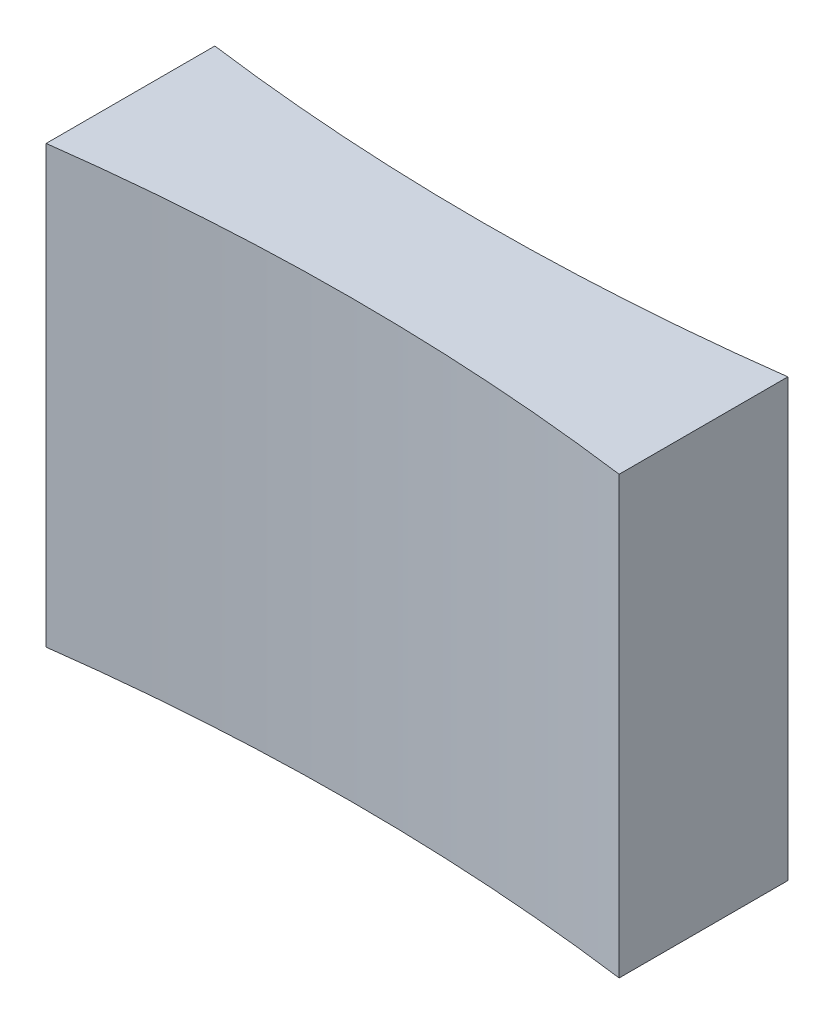
SolidWorks part; units mm, degrees
ref_plane "Front Plane" through (0, 0, 0) normal (0, 0, 1) x (1, 0, 0)
ref_plane "Top Plane" through (0, 0, 0) normal (0, 1, 0) x (1, 0, 0)
ref_plane "Right Plane" through (0, 0, 0) normal (1, 0, 0) x (0, 0, -1)
sketch "Sketch2" plane through (0, 0, 0) normal (0, 1, 0) x (1, 0, 0)
  line L0 (13.1344, -3.8671) -> (13.1344, 3.8671)
  line L1 (-13.1344, 3.8671) -> (-13.1344, -3.8671)
  line L2 (-13.1344, -3.8671) -> (-13.1344, 3.8671)
  line L3 (13.1344, 3.8671) -> (13.1344, -3.8671)
  arc A0 (13.1344, -3.8671) -> (-13.1344, -3.8671) centre (0, -102.9074) ccw
  arc A1 (-13.1344, 3.8671) -> (13.1344, 3.8671) centre (0, 102.9074) ccw
  arc A2 (-13.1344, -3.8671) -> (-29.3195, -7.399) centre (0, -102.9074) ccw
  arc A3 (-29.3195, 7.399) -> (-13.1344, 3.8671) centre (0, 102.9074) ccw
  arc A4 (-29.3195, 7.399) -> (-31.2047, 7.8764) centre (-35.047, -11.2583) ccw
  arc A5 (-31.2047, -7.8764) -> (-31.2047, 7.8764) centre (-41.547, 0) ccw
  arc A6 (-31.2047, -7.8764) -> (-29.3195, -7.399) centre (-35.047, 11.2583) ccw
  arc A7 (13.1344, 3.8671) -> (29.3195, 7.399) centre (0, 102.9074) ccw
  arc A8 (29.3195, -7.399) -> (13.1344, -3.8671) centre (0, -102.9074) ccw
  arc A9 (29.3195, -7.399) -> (31.2047, -7.8764) centre (35.047, 11.2583) ccw
  arc A10 (31.2047, 7.8764) -> (31.2047, -7.8764) centre (41.547, 0) ccw
  arc A11 (31.2047, 7.8764) -> (29.3195, 7.399) centre (35.047, -11.2583) ccw
extrude "Boss-Extrude1" add sketch "Sketch2" along normal blind 9 contours A1 L1 A0 L0
sketch "Sketch3" plane through (0, 9, 0) normal (0, 1, 0) x (1, 0, 0)
  line L1 (-13.1344, -3.8671) -> (-13.1344, 3.8671)
  line L2 (13.1344, -3.8671) -> (13.1344, 3.8671)
  line L3 (-13.1344, 3.8671) -> (-13.1344, -3.8671)
  line L4 (13.1344, -3.8671) -> (13.1344, 3.8671)
  line L5 (-13.1344, 3.8671) -> (-13.1344, -3.8671)
  line L6 (-13.1344, -3.8671) -> (-13.1344, 3.8671)
  line L7 (13.1344, 3.8671) -> (13.1344, -3.8671)
  line L8 (13.1344, 3.8671) -> (13.1344, -3.8671)
  arc A2 (-13.1344, 3.8671) -> (13.1344, 3.8671) centre (0, 102.9074) ccw
  arc A3 (13.1344, -3.8671) -> (-13.1344, -3.8671) centre (0, -102.9074) ccw
  arc A4 (-13.1344, 3.8671) -> (13.1344, 3.8671) centre (0, 102.9074) ccw
  arc A5 (13.1344, -3.8671) -> (-13.1344, -3.8671) centre (0, -102.9074) ccw
  arc A9 (-31.2047, -7.8764) -> (-31.2047, 7.8764) centre (-41.547, 0) ccw
  arc A10 (-29.3195, 7.399) -> (-31.2047, 7.8764) centre (-35.047, -11.2583) ccw
  arc A11 (-29.3195, 7.399) -> (-13.1344, 3.8671) centre (0, 102.9074) ccw
  arc A12 (-13.1344, -3.8671) -> (-29.3195, -7.399) centre (0, -102.9074) ccw
  arc A13 (-31.2047, -7.8764) -> (-29.3195, -7.399) centre (-35.047, 11.2583) ccw
  arc A14 (-31.2047, -7.8764) -> (-31.2047, 7.8764) centre (-41.547, 0) ccw
  arc A15 (-29.3195, 7.399) -> (-31.2047, 7.8764) centre (-35.047, -11.2583) ccw
  arc A16 (-29.3195, 7.399) -> (-13.1344, 3.8671) centre (0, 102.9074) ccw
  arc A17 (-13.1344, -3.8671) -> (-29.3195, -7.399) centre (0, -102.9074) ccw
  arc A18 (-31.2047, -7.8764) -> (-29.3195, -7.399) centre (-35.047, 11.2583) ccw
  arc A19 (29.3195, -7.399) -> (13.1344, -3.8671) centre (0, -102.9074) ccw
  arc A20 (29.3195, -7.399) -> (31.2047, -7.8764) centre (35.047, 11.2583) ccw
  arc A21 (31.2047, 7.8764) -> (31.2047, -7.8764) centre (41.547, 0) ccw
  arc A22 (31.2047, 7.8764) -> (29.3195, 7.399) centre (35.047, -11.2583) ccw
  arc A23 (13.1344, 3.8671) -> (29.3195, 7.399) centre (0, 102.9074) ccw
  arc A24 (29.3195, -7.399) -> (13.1344, -3.8671) centre (0, -102.9074) ccw
  arc A25 (29.3195, -7.399) -> (31.2047, -7.8764) centre (35.047, 11.2583) ccw
  arc A26 (31.2047, 7.8764) -> (31.2047, -7.8764) centre (41.547, 0) ccw
  arc A27 (31.2047, 7.8764) -> (29.3195, 7.399) centre (35.047, -11.2583) ccw
  arc A28 (13.1344, 3.8671) -> (29.3195, 7.399) centre (0, 102.9074) ccw
  arc M17 (13.1344, 3.8671) -> (-13.1344, 3.8671) centre (0, 102.9074) cw
  line M18 (-13.1344, 3.8671) -> (-13.1344, -3.8671)
  arc M19 (-13.1344, -3.8671) -> (13.1344, -3.8671) centre (0, -102.9074) cw
  line M20 (13.1344, -3.8671) -> (13.1344, 3.8671)
  dimension "D1" = 0
  dimension "D2" = 0
  dimension "D3" = 0
extrude "Boss-Extrude2" add sketch "Sketch3" along normal blind 11 contours M20 M17 M18 M19
sketch "Sketch4" plane through (0, 0, 0) normal (0, -1, 0) x (1, 0, 0)
  line L0 (0, 3) -> (0, -3) construction
  line L1 (-7.5, 2.5) -> (7.5, 2.5)
  line L2 (-7.5, 2.5) -> (-7.5, -2.5)
  line L3 (-7.5, -2.5) -> (7.5, -2.5)
  line L4 (7.5, 2.5) -> (7.5, -2.5)
  line L5 (-13.1344, 0) -> (13.1344, 0) construction
  line L6 (-13.1344, -3.8671) -> (-13.1344, 3.8671) construction
  line L8 (13.1344, 3.8671) -> (13.1344, -3.8671) construction
  arc A0 (-13.1344, 3.8671) -> (13.1344, 3.8671) centre (0, 102.9074) ccw construction
  arc A1 (13.1344, -3.8671) -> (-13.1344, -3.8671) centre (0, -102.9074) ccw construction
  point P16 (13.1344, 0)
  point P18 (13.1344, 0)
  dimension "D1" = 5
  dimension "D2" = 15
extrude "Cut-Extrude1" cut sketch "Sketch4" against normal blind 3
